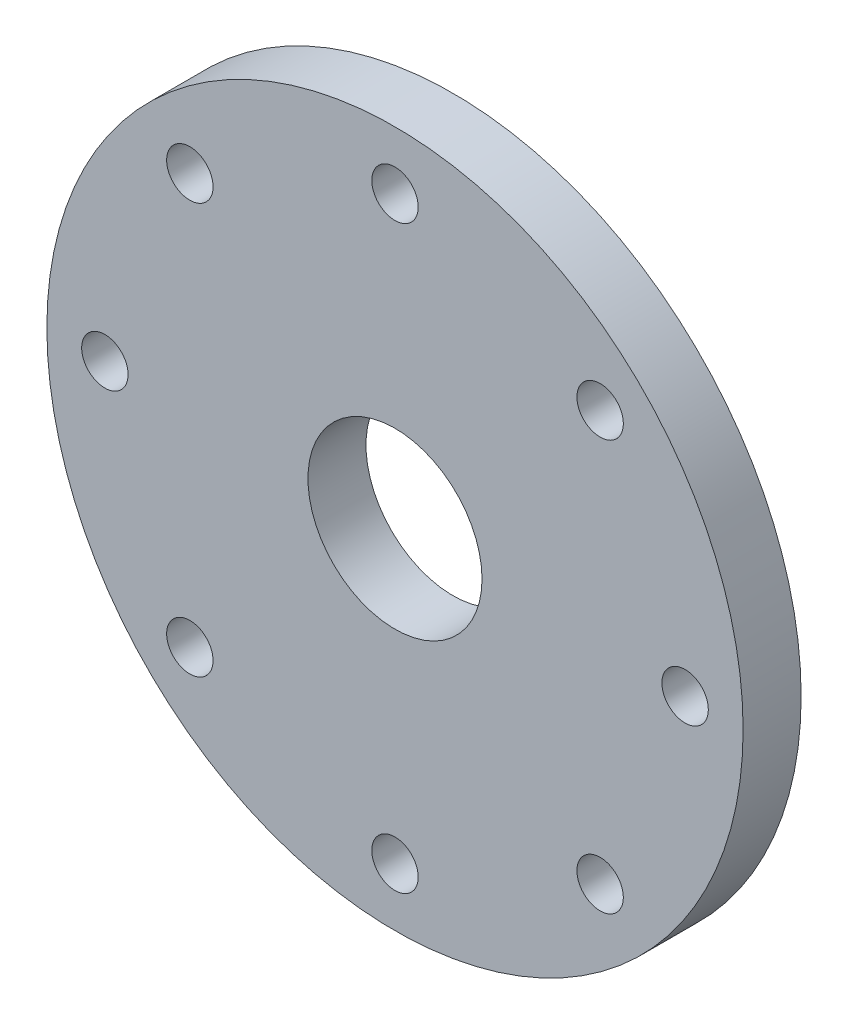
SolidWorks part; units mm, degrees
material "6061-T6 (SS)"
ref_plane "Front Plane" through (0, 0, 0) normal (0, 0, 1) x (1, 0, 0)
ref_plane "Top Plane" through (0, 0, 0) normal (0, 1, 0) x (1, 0, 0)
ref_plane "Right Plane" through (0, 0, 0) normal (1, 0, 0) x (0, 0, -1)
sketch "Sketch1" plane through (0, 0, 0) normal (0, 0, 1) x (1, 0, 0)
  circle A0 centre (0, 0) radius 15.875 construction
  circle A1 centre (0, 15.875) radius 1.27
  circle A2 centre (11.2253, 11.2253) radius 1.27
  circle A3 centre (15.875, 0) radius 1.27
  circle A4 centre (0, 0) radius 19.05
  circle A5 centre (0, 0) radius 4.7625
  circle A6 centre (11.2253, -11.2253) radius 1.27
  circle A7 centre (0, -15.875) radius 1.27
  circle A8 centre (-11.2253, -11.2253) radius 1.27
  circle A9 centre (-15.875, 0) radius 1.27
  circle A10 centre (-11.2253, 11.2253) radius 1.27
  dimension "D2" = 2.54
  dimension "D3" = 8
  dimension "D5" = 38.1
  dimension "D6" = 9.525
  dimension "D1" = 31.75
extrude "Boss-Extrude1" add sketch "Sketch1" along normal blind 3.175
